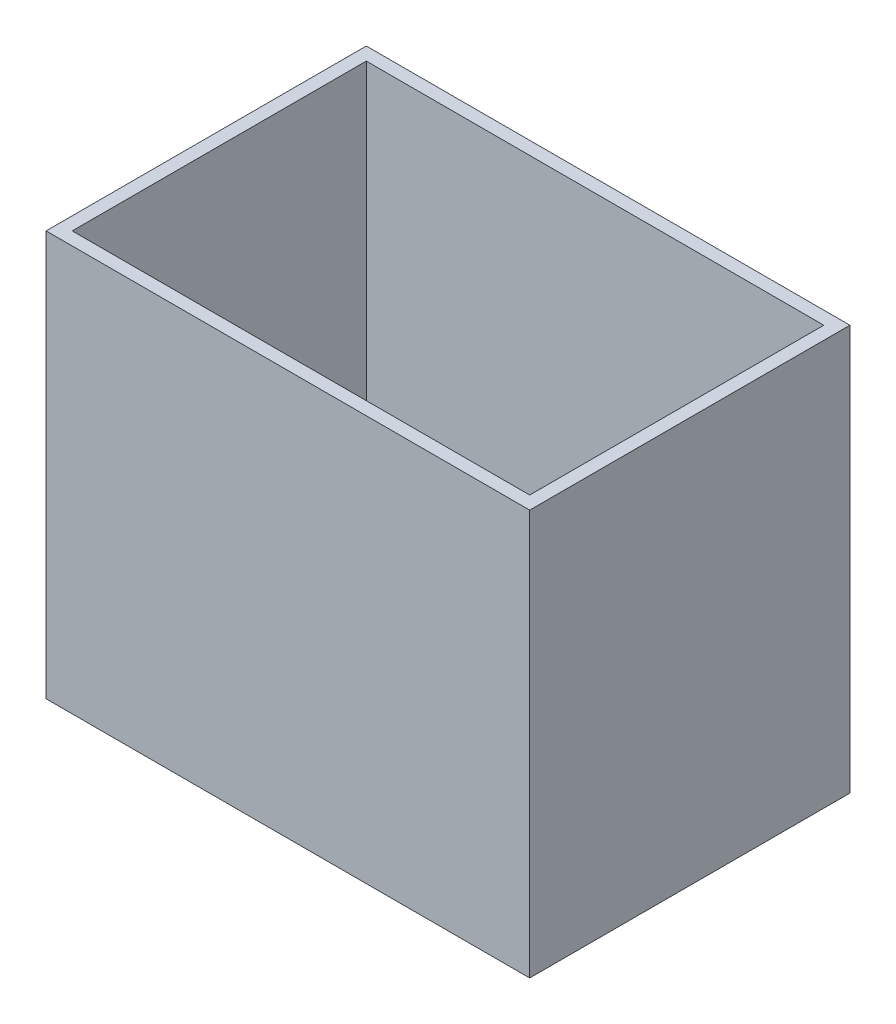
SolidWorks part; units mm, degrees
ref_plane "Front Plane" through (0, 0, 0) normal (0, 0, 1) x (1, 0, 0)
ref_plane "Top Plane" through (0, 0, 0) normal (0, 1, 0) x (1, 0, 0)
ref_plane "Right Plane" through (0, 0, 0) normal (1, 0, 0) x (0, 0, -1)
sketch "Sketch1" plane through (0, 0, 0) normal (0, 1, 0) x (1, 0, 0)
  line L1 (-185, -122.5) -> (185, -122.5)
  line L2 (-185, -122.5) -> (-185, 122.5)
  line L3 (-185, 122.5) -> (185, 122.5)
  line L4 (185, -122.5) -> (185, 122.5)
  line L5 (-185, -122.5) -> (185, 122.5) construction
  line L6 (-185, 122.5) -> (185, -122.5) construction
  point P0 (0, 0)
  dimension "D1" = 370
  dimension "D2" = 245
extrude "Boss-Extrude1" add sketch "Sketch1" along normal blind 10
sketch "Sketch2" plane through (0, 10, 0) normal (0, 1, 0) x (1, 0, 0)
  line L10 (-175, -72.5) -> (175, -72.5)
  line L11 (-175, -67.5) -> (175, -67.5)
  line L13 (-185, -122.5) -> (185, -122.5)
  line L14 (-175, -112.5) -> (175, -112.5)
  line L15 (175, -112.5) -> (175, 112.5)
  line L16 (175, 112.5) -> (-175, 112.5)
  line L17 (-175, 112.5) -> (-175, -112.5)
  line L18 (-175, -112.5) -> (175, -112.5)
  line L19 (175, -112.5) -> (175, 112.5)
  line L20 (175, 112.5) -> (-175, 112.5)
  line L21 (-175, 112.5) -> (-175, -112.5)
  line L22 (-185, -122.5) -> (-185, 122.5)
  line L23 (-185, 122.5) -> (185, 122.5)
  line L24 (185, -122.5) -> (185, 122.5)
  line L25 (-185, -122.5) -> (185, 122.5) construction
  line L26 (-185, 122.5) -> (185, -122.5) construction
  point P4 (0, 0)
  line M5 (185, -122.5) -> (185, 122.5)
  line M6 (185, 122.5) -> (-185, 122.5)
  line M7 (-185, 122.5) -> (-185, -122.5)
  line M8 (-185, -122.5) -> (185, -122.5)
  dimension "D2" = 40
  dimension "D3" = 5
  dimension "D1" = 10
extrude "Boss-Extrude3" add sketch "Sketch2" along normal blind 300 contours L21 L20 L19 L18 M8 M5 M6 M7 | L11 L21 L10 L19
sketch "Sketch3" plane through (0, 310, 0) normal (0, 1, 0) x (1, 0, 0)
  line L0 (175, -67.5) -> (175, -72.5)
  line L1 (-175, -67.5) -> (-175, -72.5)
  line L2 (175, -67.5) -> (-175, -67.5)
  line L3 (-175, -72.5) -> (175, -72.5)
extrude "Cut-Extrude1" cut sketch "Sketch3" against normal blind 45
